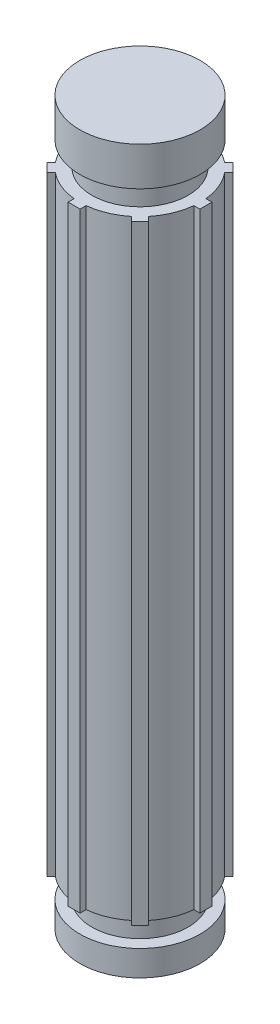
SolidWorks part; units mm, degrees
material "1060 Alloy"
ref_plane "Front Plane" through (0, 0, 0) normal (0, 0, 1) x (1, 0, 0)
ref_plane "Top Plane" through (0, 0, 0) normal (0, 1, 0) x (1, 0, 0)
ref_plane "Right Plane" through (0, 0, 0) normal (1, 0, 0) x (0, 0, -1)
sketch "Sketch3" plane through (0, 0, 0) normal (1, 0, 0) x (0, 0, -1)
  line L1 (0, 0) -> (10, 0)
  line L2 (0, 0) -> (0, 120)
  line L3 (0, 120) -> (10, 120)
  line L4 (10, 0) -> (10, 120)
  line L5 (10, 4.2435) -> (8, 4.2435)
  line L6 (10, 4.2435) -> (10, 8.2435)
  line L7 (10, 8.2435) -> (8, 8.2435)
  line L8 (8, 4.2435) -> (8, 8.2435)
  line L9 (10, 113.5686) -> (8, 113.5686)
  line L10 (10, 113.5686) -> (10, 109.5686)
  line L11 (10, 109.5686) -> (8, 109.5686)
  line L12 (8, 113.5686) -> (8, 109.5686)
  dimension "D1" = 120
  dimension "D2" = 10
  dimension "D3" = 2
  dimension "D4" = 4
revolve "Revolve1" add sketch "Sketch3" angle 360 about L2
sketch "Sketch4" plane through (0, 0, 0) normal (0, -1, 0) x (1, 0, 0)
  line L0 (-1, 9.9499) -> (-1, 10.9499)
  line L1 (-1, 10.9499) -> (1, 10.9499)
  line L2 (1, 10.9499) -> (1, 9.9499)
  line L3 (0, 0) -> (0, 15.0182) construction
  circle A0 centre (0, 0) radius 10 construction
  arc A1 (-1, 9.9499) -> (1, 9.9499) centre (0, 0) cw
  point P11 (-1.369, 11.048)
  point P12 (1.5745, 9.8753)
  dimension "D1" = 2
  dimension "D2" = 1
extrude "Boss-Extrude2" add sketch "Sketch4" along normal up to surface (101.3251 mm away) from surface
pattern_circular "CirPattern1" count 8 over 360 about axis through (0, 0, 0) along (0, 1, 0) of "Boss-Extrude2"
